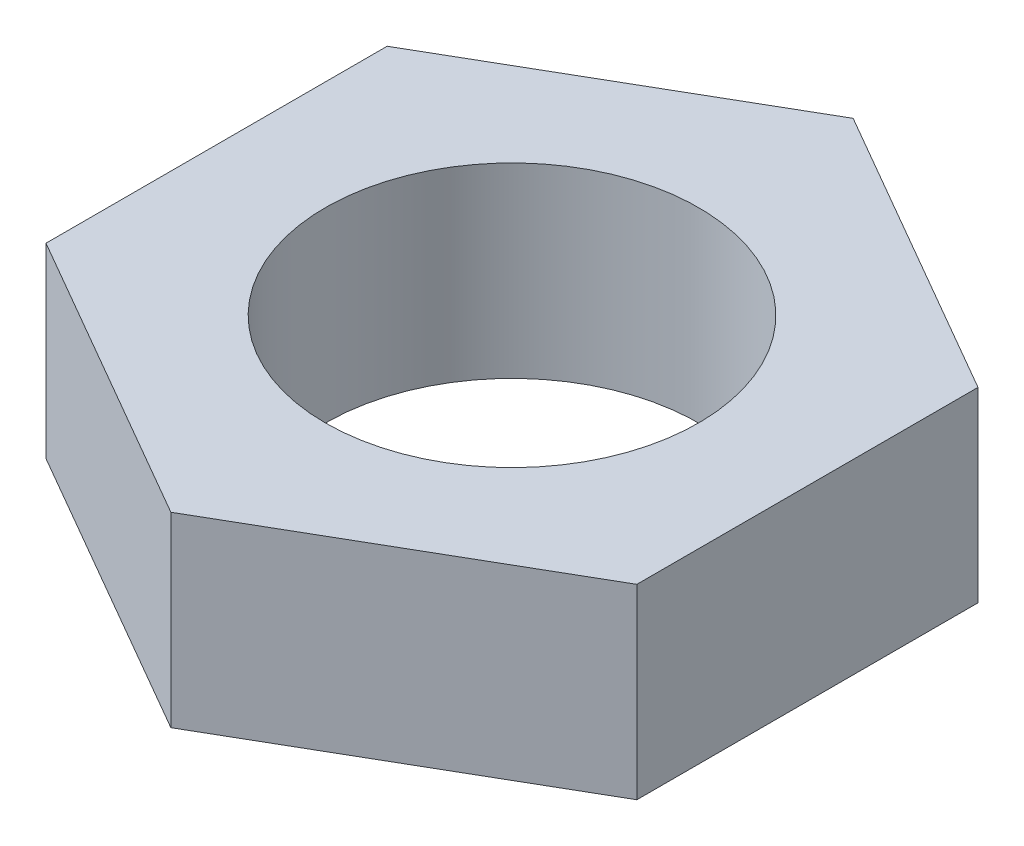
SolidWorks part; units mm, degrees
ref_plane "Front Plane" through (0, 0, 0) normal (0, 0, 1) x (1, 0, 0)
ref_plane "Top Plane" through (0, 0, 0) normal (0, 1, 0) x (1, 0, 0)
ref_plane "Right Plane" through (0, 0, 0) normal (1, 0, 0) x (0, 0, -1)
sketch "Sketch1" plane through (0, 0, 0) normal (0, 1, 0) x (1, 0, 0)
  line L1 (0, 10.9697) -> (-9.5, 5.4848)
  line L2 (-9.5, 5.4848) -> (-9.5, -5.4848)
  line L3 (-9.5, -5.4848) -> (0, -10.9697)
  line L4 (0, -10.9697) -> (9.5, -5.4848)
  line L5 (9.5, -5.4848) -> (9.5, 5.4848)
  line L6 (9.5, 5.4848) -> (0, 10.9697)
  circle A0 centre (0, 0) radius 9.5 construction
  circle A1 centre (0, 0) radius 6
  dimension "D2" = 12
  dimension "D1" = 19
extrude "Boss-Extrude1" add sketch "Sketch1" along normal blind 6
